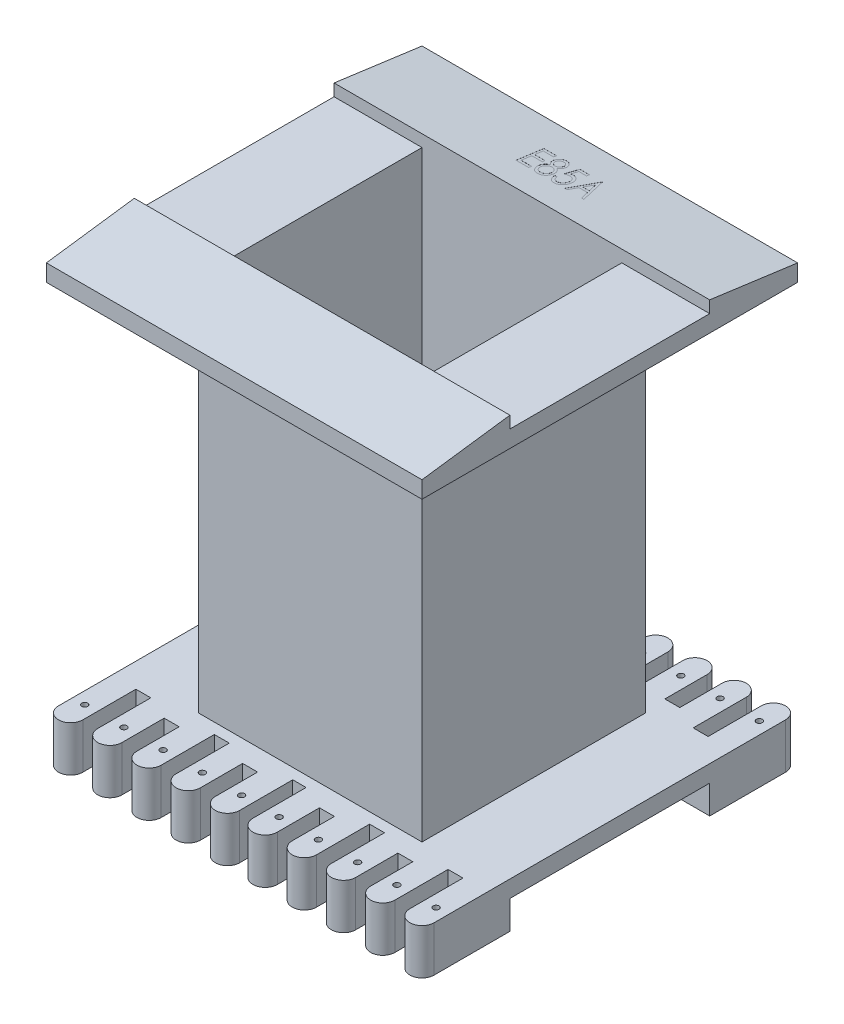
SolidWorks part; units mm, degrees
material "ABS"
ref_plane "Front Plane" through (0, 0, 0) normal (0, 0, 1) x (1, 0, 0)
ref_plane "Top Plane" through (0, 0, 0) normal (0, 1, 0) x (1, 0, 0)
ref_plane "Right Plane" through (0, 0, 0) normal (1, 0, 0) x (0, 0, -1)
sketch "Sketch2" plane through (0, 0, 0) normal (0, 1, 0) x (1, 0, 0)
  line L1 (-15.9, 15.9) -> (15.9, 15.9)
  line L2 (-15.9, 15.9) -> (-15.9, -15.9)
  line L3 (-15.9, -15.9) -> (15.9, -15.9)
  line L4 (15.9, 15.9) -> (15.9, -15.9)
  line L5 (-15.9, 15.9) -> (15.9, -15.9) construction
  line L6 (-15.9, -15.9) -> (15.9, 15.9) construction
  line L7 (-14.2, 14.2) -> (14.2, 14.2)
  line L8 (-14.2, 14.2) -> (-14.2, -14.2)
  line L9 (-14.2, -14.2) -> (14.2, -14.2)
  line L10 (14.2, 14.2) -> (14.2, -14.2)
  line L11 (-14.2, 14.2) -> (14.2, -14.2) construction
  line L12 (-14.2, -14.2) -> (14.2, 14.2) construction
  point P0 (0, 0)
  point P5 (0, 0)
  dimension "D1" = 31.8
  dimension "D2" = 28.4
extrude "Boss-Extrude1" add sketch "Sketch2" along normal mid plane 53
sketch "Sketch4" plane through (0, 26.5, 0) normal (0, 1, 0) x (1, 0, 0)
  line L0 (-14.2, -14.2) -> (14.2, -14.2) construction
  line L1 (-26.7, -26.7) -> (26.7, -26.7)
  line L2 (-26.7, -26.7) -> (-26.7, 26.7)
  line L3 (-26.7, 26.7) -> (26.7, 26.7)
  line L4 (26.7, -26.7) -> (26.7, 26.7)
  line L5 (-26.7, -26.7) -> (26.7, 26.7) construction
  line L6 (-26.7, 26.7) -> (26.7, -26.7) construction
  line L7 (-14.2, 14.2) -> (-14.2, -14.2) construction
  line L8 (14.2, 14.2) -> (-14.2, 14.2) construction
  line L9 (14.2, -14.2) -> (14.2, 14.2) construction
  line L10 (-14.2, -14.2) -> (14.2, -14.2)
  line L11 (-14.2, 14.2) -> (-14.2, -14.2)
  line L12 (14.2, 14.2) -> (-14.2, 14.2)
  line L13 (14.2, -14.2) -> (14.2, 14.2)
  point P0 (0, 0)
  dimension "D1" = 53.4
  dimension "D2" = 53.4
extrude "Boss-Extrude2" add sketch "Sketch4" along normal blind 2.4
mirror "Mirror1" about plane through (0, 0, 0) normal (0, 1, 0) of "Boss-Extrude2"
sketch "Sketch5" plane through (0, 0, 0) normal (1, 0, 0) x (0, 0, -1)
  line L0 (-26.7, 28.9) -> (-14.2, 30.6)
  line L2 (-26.7, 28.9) -> (26.7, 28.9) construction
  line L3 (-14.2, 30.6) -> (-14.2, 28.9)
  line L4 (-14.2, 28.9) -> (-26.7, 28.9)
  line L5 (0, 0) -> (0, 38.1311) construction
  line L6 (14.2, 30.6) -> (14.2, 28.9)
  line L7 (26.7, 28.9) -> (14.2, 30.6)
  line L8 (14.2, 28.9) -> (26.7, 28.9)
  line L9 (-14.2, 28.9) -> (-14.2, -28.9) construction
  dimension "D1" = 1.7
extrude "Boss-Extrude3" add sketch "Sketch5" along normal mid plane 53.4
sketch "Sketch7" plane through (0, -28.9, 0) normal (0, -1, 0) x (1, 0, 0)
  line L0 (0, 35.9012) -> (0, -6.2706) construction
  line L1 (-26.7, 26.7) -> (-26.7, 24.975)
  line L2 (-26.7, -26.7) -> (-26.7, 26.7) construction
  line L3 (-26.7, 26.7) -> (26.7, 26.7) construction
  line L4 (-26.7, 26.7) -> (-26.7, 27.95)
  line L5 (-26.7, 27.95) -> (26.7, 27.95)
  line L6 (-12.1, 24.975) -> (-12.1, 17.425)
  line L7 (26.7, 24.975) -> (-16.1388, 24.975) construction
  line L20 (-23.25, 24.975) -> (-23.25, 17.425)
  line L21 (-23.25, 17.425) -> (-21.125, 17.425)
  line L22 (-21.125, 17.425) -> (-21.125, 24.975)
  line L23 (-21.125, 24.975) -> (-23.25, 24.975) construction
  line L24 (-23.25, 24.975) -> (-26.7, 24.975) construction
  line L28 (-6.525, 24.975) -> (-6.525, 18.975)
  line L29 (-16.1388, 24.975) -> (-21.125, 24.975) construction
  line L30 (-9.975, 17.425) -> (-9.975, 24.975)
  line L31 (-12.1, 17.425) -> (-9.975, 17.425)
  line L32 (-17.675, 24.975) -> (-17.675, 18.975)
  line L33 (-17.675, 18.975) -> (-15.55, 18.975)
  line L34 (-15.55, 18.975) -> (-15.55, 24.975)
  line L35 (-6.525, 18.975) -> (-4.4, 18.975)
  line L36 (-4.4, 18.975) -> (-4.4, 24.975)
  line L37 (16.1388, 24.975) -> (21.125, 24.975) construction
  line L38 (23.25, 24.975) -> (26.7, 24.975) construction
  line L39 (21.125, 24.975) -> (23.25, 24.975) construction
  line L40 (4.4, 18.975) -> (4.4, 24.975)
  line L41 (6.525, 18.975) -> (4.4, 18.975)
  line L42 (15.55, 18.975) -> (15.55, 24.975)
  line L43 (17.675, 18.975) -> (15.55, 18.975)
  line L44 (17.675, 24.975) -> (17.675, 18.975)
  line L45 (12.1, 17.425) -> (9.975, 17.425)
  line L46 (9.975, 17.425) -> (9.975, 24.975)
  line L47 (6.525, 24.975) -> (6.525, 18.975)
  line L48 (21.125, 17.425) -> (21.125, 24.975)
  line L49 (23.25, 17.425) -> (21.125, 17.425)
  line L50 (23.25, 24.975) -> (23.25, 17.425)
  line L51 (12.1, 24.975) -> (12.1, 17.425)
  line L53 (26.7, 27.95) -> (26.7, 24.975)
  line L55 (-0.95, 24.975) -> (-0.95, 17.425)
  line L56 (-0.95, 17.425) -> (0.95, 17.425)
  line L57 (0.95, 17.425) -> (0.95, 24.975)
  line L58 (-24.975, 23.4) -> (-26.02, 23.4) construction
  line L60 (-14.2, 14.2) -> (14.2, 14.2) construction
  line L61 (0, 0) -> (-5.5861, 0) construction
  line L62 (-24.975, -23.4) -> (-26.02, -23.4) construction
  line L63 (21.125, -24.975) -> (23.25, -24.975) construction
  line L64 (23.25, -24.975) -> (26.7, -24.975) construction
  line L65 (16.1388, -24.975) -> (21.125, -24.975) construction
  line L66 (-16.1388, -24.975) -> (-21.125, -24.975) construction
  line L67 (-23.25, -24.975) -> (-26.7, -24.975) construction
  line L68 (-21.125, -24.975) -> (-23.25, -24.975) construction
  line L69 (26.7, -24.975) -> (-16.1388, -24.975) construction
  line L70 (0.95, -17.425) -> (0.95, -24.975)
  line L71 (-0.95, -17.425) -> (0.95, -17.425)
  line L72 (-0.95, -24.975) -> (-0.95, -17.425)
  line L73 (26.7, -27.95) -> (26.7, -24.975)
  line L74 (12.1, -24.975) -> (12.1, -17.425)
  line L75 (23.25, -24.975) -> (23.25, -17.425)
  line L76 (23.25, -17.425) -> (21.125, -17.425)
  line L77 (21.125, -17.425) -> (21.125, -24.975)
  line L78 (6.525, -24.975) -> (6.525, -18.975)
  line L79 (9.975, -17.425) -> (9.975, -24.975)
  line L80 (12.1, -17.425) -> (9.975, -17.425)
  line L81 (17.675, -24.975) -> (17.675, -18.975)
  line L82 (17.675, -18.975) -> (15.55, -18.975)
  line L83 (15.55, -18.975) -> (15.55, -24.975)
  line L84 (6.525, -18.975) -> (4.4, -18.975)
  line L85 (4.4, -18.975) -> (4.4, -24.975)
  line L86 (-4.4, -18.975) -> (-4.4, -24.975)
  line L87 (-6.525, -18.975) -> (-4.4, -18.975)
  line L88 (-15.55, -18.975) -> (-15.55, -24.975)
  line L89 (-17.675, -18.975) -> (-15.55, -18.975)
  line L90 (-17.675, -24.975) -> (-17.675, -18.975)
  line L91 (-12.1, -17.425) -> (-9.975, -17.425)
  line L92 (-9.975, -17.425) -> (-9.975, -24.975)
  line L93 (-6.525, -24.975) -> (-6.525, -18.975)
  line L94 (-21.125, -17.425) -> (-21.125, -24.975)
  line L95 (-23.25, -17.425) -> (-21.125, -17.425)
  line L96 (-23.25, -24.975) -> (-23.25, -17.425)
  line L97 (-12.1, -24.975) -> (-12.1, -17.425)
  line L98 (-26.7, -27.95) -> (26.7, -27.95)
  line L99 (-26.7, -26.7) -> (-26.7, -27.95)
  line L100 (-26.7, -26.7) -> (-26.7, -24.975)
  arc A0 (-26.7, 24.975) -> (-23.25, 24.975) centre (-24.975, 24.975) cw
  arc A11 (-21.125, 24.975) -> (-17.675, 24.975) centre (-19.4, 24.975) cw
  arc A12 (-15.55, 24.975) -> (-12.1, 24.975) centre (-13.825, 24.975) cw
  arc A13 (-9.975, 24.975) -> (-6.525, 24.975) centre (-8.25, 24.975) cw
  arc A14 (-4.4, 24.975) -> (-0.95, 24.975) centre (-2.675, 24.975) cw
  arc A15 (4.4, 24.975) -> (0.95, 24.975) centre (2.675, 24.975) ccw
  arc A16 (9.975, 24.975) -> (6.525, 24.975) centre (8.25, 24.975) ccw
  arc A17 (15.55, 24.975) -> (12.1, 24.975) centre (13.825, 24.975) ccw
  arc A18 (21.125, 24.975) -> (17.675, 24.975) centre (19.4, 24.975) ccw
  arc A19 (26.7, 24.975) -> (23.25, 24.975) centre (24.975, 24.975) ccw
  circle A20 centre (-24.975, 22.975) radius 0.425
  circle A21 centre (-19.4, 22.975) radius 0.425
  circle A22 centre (-13.825, 22.975) radius 0.425
  circle A23 centre (-8.25, 22.975) radius 0.425
  circle A24 centre (-2.675, 22.975) radius 0.425
  circle A25 centre (19.4, 22.975) radius 0.425
  circle A26 centre (13.825, 22.975) radius 0.425
  circle A27 centre (8.25, 22.975) radius 0.425
  circle A28 centre (2.675, 22.975) radius 0.425
  circle A29 centre (24.975, 22.975) radius 0.425
  circle A30 centre (24.975, -22.975) radius 0.425
  circle A31 centre (2.675, -22.975) radius 0.425
  circle A32 centre (8.25, -22.975) radius 0.425
  circle A33 centre (13.825, -22.975) radius 0.425
  circle A34 centre (19.4, -22.975) radius 0.425
  circle A35 centre (-2.675, -22.975) radius 0.425
  circle A36 centre (-8.25, -22.975) radius 0.425
  circle A37 centre (-13.825, -22.975) radius 0.425
  circle A38 centre (-19.4, -22.975) radius 0.425
  circle A39 centre (-24.975, -22.975) radius 0.425
  arc A40 (26.7, -24.975) -> (23.25, -24.975) centre (24.975, -24.975) cw
  arc A41 (21.125, -24.975) -> (17.675, -24.975) centre (19.4, -24.975) cw
  arc A42 (15.55, -24.975) -> (12.1, -24.975) centre (13.825, -24.975) cw
  arc A43 (9.975, -24.975) -> (6.525, -24.975) centre (8.25, -24.975) cw
  arc A44 (4.4, -24.975) -> (0.95, -24.975) centre (2.675, -24.975) cw
  arc A45 (-4.4, -24.975) -> (-0.95, -24.975) centre (-2.675, -24.975) ccw
  arc A46 (-9.975, -24.975) -> (-6.525, -24.975) centre (-8.25, -24.975) ccw
  arc A47 (-15.55, -24.975) -> (-12.1, -24.975) centre (-13.825, -24.975) ccw
  arc A48 (-21.125, -24.975) -> (-17.675, -24.975) centre (-19.4, -24.975) ccw
  arc A49 (-26.7, -24.975) -> (-23.25, -24.975) centre (-24.975, -24.975) ccw
  dimension "D1" = 3.3
  dimension "D6" = 1.25
  dimension "D8" = 0.85
  dimension "D2" = 3.225
  dimension "D3" = 1.55
  dimension "D4" = 6
  dimension "D5" = 2.125
  dimension "D7" = 2
  dimension "D9" = 5
extrude "Cut-Extrude1" cut sketch "Sketch7" against normal blind 3
sketch "Sketch8" plane through (0, -28.9, 0) normal (0, -1, 0) x (1, 0, 0)
  line L0 (-26.7, 14.2) -> (26.7, 14.2)
  line L1 (26.7, 24.975) -> (26.7, -24.975) construction
  line L2 (0, 0) -> (-9.975, 0) construction
  line L3 (-26.7, -24.975) -> (-26.7, -14.2)
  line L8 (-23.25, -17.425) -> (-23.25, -24.975)
  line L9 (-21.125, -17.425) -> (-23.25, -17.425)
  line L10 (-21.125, -24.975) -> (-21.125, -17.425)
  line L11 (-17.675, -18.975) -> (-17.675, -24.975)
  line L12 (-15.55, -18.975) -> (-17.675, -18.975)
  line L13 (-15.55, -24.975) -> (-15.55, -18.975)
  line L14 (-12.1, -17.425) -> (-12.1, -24.975)
  line L15 (-9.975, -17.425) -> (-12.1, -17.425)
  line L16 (-9.975, -24.975) -> (-9.975, -17.425)
  line L17 (-6.525, -18.975) -> (-6.525, -24.975)
  line L18 (-4.4, -18.975) -> (-6.525, -18.975)
  line L19 (-4.4, -24.975) -> (-4.4, -18.975)
  line L20 (-0.95, -17.425) -> (-0.95, -24.975)
  line L21 (0.95, -17.425) -> (-0.95, -17.425)
  line L22 (0.95, -24.975) -> (0.95, -17.425)
  line L23 (4.4, -18.975) -> (4.4, -24.975)
  line L24 (6.525, -18.975) -> (4.4, -18.975)
  line L25 (6.525, -24.975) -> (6.525, -18.975)
  line L26 (9.975, -17.425) -> (9.975, -24.975)
  line L27 (12.1, -17.425) -> (9.975, -17.425)
  line L28 (12.1, -24.975) -> (12.1, -17.425)
  line L29 (15.55, -18.975) -> (15.55, -24.975)
  line L30 (17.675, -18.975) -> (15.55, -18.975)
  line L31 (17.675, -24.975) -> (17.675, -18.975)
  line L32 (21.125, -17.425) -> (21.125, -24.975)
  line L33 (23.25, -17.425) -> (21.125, -17.425)
  line L34 (23.25, -24.975) -> (23.25, -17.425)
  line L35 (26.7, -14.2) -> (26.7, -24.975)
  line L36 (-26.7, -14.2) -> (26.7, -14.2)
  line L58 (26.7, -24.975) -> (26.7, 24.975)
  line L59 (23.25, 24.975) -> (23.25, 17.425)
  line L60 (23.25, 17.425) -> (21.125, 17.425)
  line L61 (21.125, 17.425) -> (21.125, 24.975)
  line L62 (17.675, 24.975) -> (17.675, 18.975)
  line L63 (17.675, 18.975) -> (15.55, 18.975)
  line L64 (15.55, 18.975) -> (15.55, 24.975)
  line L65 (12.1, 24.975) -> (12.1, 17.425)
  line L66 (12.1, 17.425) -> (9.975, 17.425)
  line L67 (9.975, 17.425) -> (9.975, 24.975)
  line L68 (6.525, 24.975) -> (6.525, 18.975)
  line L69 (6.525, 18.975) -> (4.4, 18.975)
  line L70 (4.4, 18.975) -> (4.4, 24.975)
  line L71 (0.95, 24.975) -> (0.95, 17.425)
  line L72 (0.95, 17.425) -> (-0.95, 17.425)
  line L73 (-0.95, 17.425) -> (-0.95, 24.975)
  line L74 (-4.4, 24.975) -> (-4.4, 18.975)
  line L75 (-4.4, 18.975) -> (-6.525, 18.975)
  line L76 (-6.525, 18.975) -> (-6.525, 24.975)
  line L77 (-9.975, 24.975) -> (-9.975, 17.425)
  line L78 (-9.975, 17.425) -> (-12.1, 17.425)
  line L79 (-12.1, 17.425) -> (-12.1, 24.975)
  line L80 (-15.55, 24.975) -> (-15.55, 18.975)
  line L81 (-15.55, 18.975) -> (-17.675, 18.975)
  line L82 (-17.675, 18.975) -> (-17.675, 24.975)
  line L83 (-21.125, 24.975) -> (-21.125, 17.425)
  line L84 (-21.125, 17.425) -> (-23.25, 17.425)
  line L85 (-23.25, 17.425) -> (-23.25, 24.975)
  line L86 (-26.7, 24.975) -> (-26.7, -24.975)
  line L87 (-23.25, -24.975) -> (-23.25, -17.425)
  line L88 (-23.25, -17.425) -> (-21.125, -17.425)
  line L89 (-21.125, -17.425) -> (-21.125, -24.975)
  line L90 (-17.675, -24.975) -> (-17.675, -18.975)
  line L91 (-17.675, -18.975) -> (-15.55, -18.975)
  line L92 (-15.55, -18.975) -> (-15.55, -24.975)
  line L93 (-12.1, -24.975) -> (-12.1, -17.425)
  line L94 (-12.1, -17.425) -> (-9.975, -17.425)
  line L95 (-9.975, -17.425) -> (-9.975, -24.975)
  line L96 (-6.525, -24.975) -> (-6.525, -18.975)
  line L97 (-6.525, -18.975) -> (-4.4, -18.975)
  line L98 (-4.4, -18.975) -> (-4.4, -24.975)
  line L99 (-0.95, -24.975) -> (-0.95, -17.425)
  line L100 (-0.95, -17.425) -> (0.95, -17.425)
  line L101 (0.95, -17.425) -> (0.95, -24.975)
  line L102 (4.4, -24.975) -> (4.4, -18.975)
  line L103 (4.4, -18.975) -> (6.525, -18.975)
  line L104 (6.525, -18.975) -> (6.525, -24.975)
  line L105 (9.975, -24.975) -> (9.975, -17.425)
  line L106 (9.975, -17.425) -> (12.1, -17.425)
  line L107 (12.1, -17.425) -> (12.1, -24.975)
  line L108 (15.55, -24.975) -> (15.55, -18.975)
  line L109 (15.55, -18.975) -> (17.675, -18.975)
  line L110 (17.675, -18.975) -> (17.675, -24.975)
  line L111 (21.125, -24.975) -> (21.125, -17.425)
  line L112 (21.125, -17.425) -> (23.25, -17.425)
  line L113 (23.25, -17.425) -> (23.25, -24.975)
  line L114 (26.7, 14.2) -> (26.7, 24.975)
  line L115 (23.25, 24.975) -> (23.25, 17.425)
  line L116 (23.25, 17.425) -> (21.125, 17.425)
  line L117 (21.125, 17.425) -> (21.125, 24.975)
  line L118 (17.675, 24.975) -> (17.675, 18.975)
  line L119 (17.675, 18.975) -> (15.55, 18.975)
  line L120 (15.55, 18.975) -> (15.55, 24.975)
  line L121 (12.1, 24.975) -> (12.1, 17.425)
  line L122 (12.1, 17.425) -> (9.975, 17.425)
  line L123 (9.975, 17.425) -> (9.975, 24.975)
  line L124 (6.525, 24.975) -> (6.525, 18.975)
  line L125 (6.525, 18.975) -> (4.4, 18.975)
  line L126 (4.4, 18.975) -> (4.4, 24.975)
  line L127 (0.95, 24.975) -> (0.95, 17.425)
  line L128 (0.95, 17.425) -> (-0.95, 17.425)
  line L129 (-0.95, 17.425) -> (-0.95, 24.975)
  line L130 (-4.4, 24.975) -> (-4.4, 18.975)
  line L131 (-4.4, 18.975) -> (-6.525, 18.975)
  line L132 (-6.525, 18.975) -> (-6.525, 24.975)
  line L133 (-9.975, 24.975) -> (-9.975, 17.425)
  line L134 (-9.975, 17.425) -> (-12.1, 17.425)
  line L135 (-12.1, 17.425) -> (-12.1, 24.975)
  line L136 (-15.55, 24.975) -> (-15.55, 18.975)
  line L137 (-15.55, 18.975) -> (-17.675, 18.975)
  line L138 (-17.675, 18.975) -> (-17.675, 24.975)
  line L139 (-21.125, 24.975) -> (-21.125, 17.425)
  line L140 (-21.125, 17.425) -> (-23.25, 17.425)
  line L141 (-23.25, 17.425) -> (-23.25, 24.975)
  line L142 (-26.7, 24.975) -> (-26.7, 14.2)
  arc A0 (-23.25, -24.975) -> (-26.7, -24.975) centre (-24.975, -24.975) cw
  arc A1 (-17.675, -24.975) -> (-21.125, -24.975) centre (-19.4, -24.975) cw
  arc A2 (-12.1, -24.975) -> (-15.55, -24.975) centre (-13.825, -24.975) cw
  arc A3 (-6.525, -24.975) -> (-9.975, -24.975) centre (-8.25, -24.975) cw
  arc A4 (-0.95, -24.975) -> (-4.4, -24.975) centre (-2.675, -24.975) cw
  arc A5 (4.4, -24.975) -> (0.95, -24.975) centre (2.675, -24.975) cw
  arc A6 (9.975, -24.975) -> (6.525, -24.975) centre (8.25, -24.975) cw
  arc A7 (15.55, -24.975) -> (12.1, -24.975) centre (13.825, -24.975) cw
  arc A8 (21.125, -24.975) -> (17.675, -24.975) centre (19.4, -24.975) cw
  arc A9 (26.7, -24.975) -> (23.25, -24.975) centre (24.975, -24.975) cw
  arc A20 (23.25, -24.975) -> (26.7, -24.975) centre (24.975, -24.975) ccw
  arc A21 (26.7, 24.975) -> (23.25, 24.975) centre (24.975, 24.975) ccw
  arc A22 (21.125, 24.975) -> (17.675, 24.975) centre (19.4, 24.975) ccw
  arc A23 (15.55, 24.975) -> (12.1, 24.975) centre (13.825, 24.975) ccw
  arc A24 (9.975, 24.975) -> (6.525, 24.975) centre (8.25, 24.975) ccw
  arc A25 (4.4, 24.975) -> (0.95, 24.975) centre (2.675, 24.975) ccw
  arc A26 (-0.95, 24.975) -> (-4.4, 24.975) centre (-2.675, 24.975) ccw
  arc A27 (-6.525, 24.975) -> (-9.975, 24.975) centre (-8.25, 24.975) ccw
  arc A28 (-12.1, 24.975) -> (-15.55, 24.975) centre (-13.825, 24.975) ccw
  arc A29 (-17.675, 24.975) -> (-21.125, 24.975) centre (-19.4, 24.975) ccw
  arc A30 (-23.25, 24.975) -> (-26.7, 24.975) centre (-24.975, 24.975) ccw
  arc A31 (-26.7, -24.975) -> (-23.25, -24.975) centre (-24.975, -24.975) ccw
  arc A32 (-21.125, -24.975) -> (-17.675, -24.975) centre (-19.4, -24.975) ccw
  arc A33 (-15.55, -24.975) -> (-12.1, -24.975) centre (-13.825, -24.975) ccw
  arc A34 (-9.975, -24.975) -> (-6.525, -24.975) centre (-8.25, -24.975) ccw
  arc A35 (-4.4, -24.975) -> (-0.95, -24.975) centre (-2.675, -24.975) ccw
  arc A36 (0.95, -24.975) -> (4.4, -24.975) centre (2.675, -24.975) ccw
  arc A37 (6.525, -24.975) -> (9.975, -24.975) centre (8.25, -24.975) ccw
  arc A38 (12.1, -24.975) -> (15.55, -24.975) centre (13.825, -24.975) ccw
  arc A39 (17.675, -24.975) -> (21.125, -24.975) centre (19.4, -24.975) ccw
  arc A41 (26.7, 24.975) -> (23.25, 24.975) centre (24.975, 24.975) ccw
  arc A42 (21.125, 24.975) -> (17.675, 24.975) centre (19.4, 24.975) ccw
  arc A43 (15.55, 24.975) -> (12.1, 24.975) centre (13.825, 24.975) ccw
  arc A44 (9.975, 24.975) -> (6.525, 24.975) centre (8.25, 24.975) ccw
  arc A45 (4.4, 24.975) -> (0.95, 24.975) centre (2.675, 24.975) ccw
  arc A46 (-0.95, 24.975) -> (-4.4, 24.975) centre (-2.675, 24.975) ccw
  arc A47 (-6.525, 24.975) -> (-9.975, 24.975) centre (-8.25, 24.975) ccw
  arc A48 (-12.1, 24.975) -> (-15.55, 24.975) centre (-13.825, 24.975) ccw
  arc A49 (-17.675, 24.975) -> (-21.125, 24.975) centre (-19.4, 24.975) ccw
  arc A50 (-23.25, 24.975) -> (-26.7, 24.975) centre (-24.975, 24.975) ccw
  dimension "D1" = 0
extrude "Boss-Extrude4" add sketch "Sketch8" along normal blind 4.05
sketch "Sketch9" plane through (0, 31.9404, -4.3439) normal (0, 0.9909, -0.1348) x (1, 0, 0)
  line L0 (-26.7, 13.9468) -> (26.7, 13.9468) construction
  line L1 (-26.7, 22.5619) -> (-26.7, 9.9468) construction
  line L2 (26.7, 22.5619) -> (26.7, 9.9468) construction
  line L3 (26.7, 9.9468) -> (-26.7, 9.9468) construction
  text T0 "E85A" font "Century Gothic" height 4
  dimension "D1" = 4
extrude "Cut-Extrude2" cut sketch "Sketch9" against normal blind 0.01
